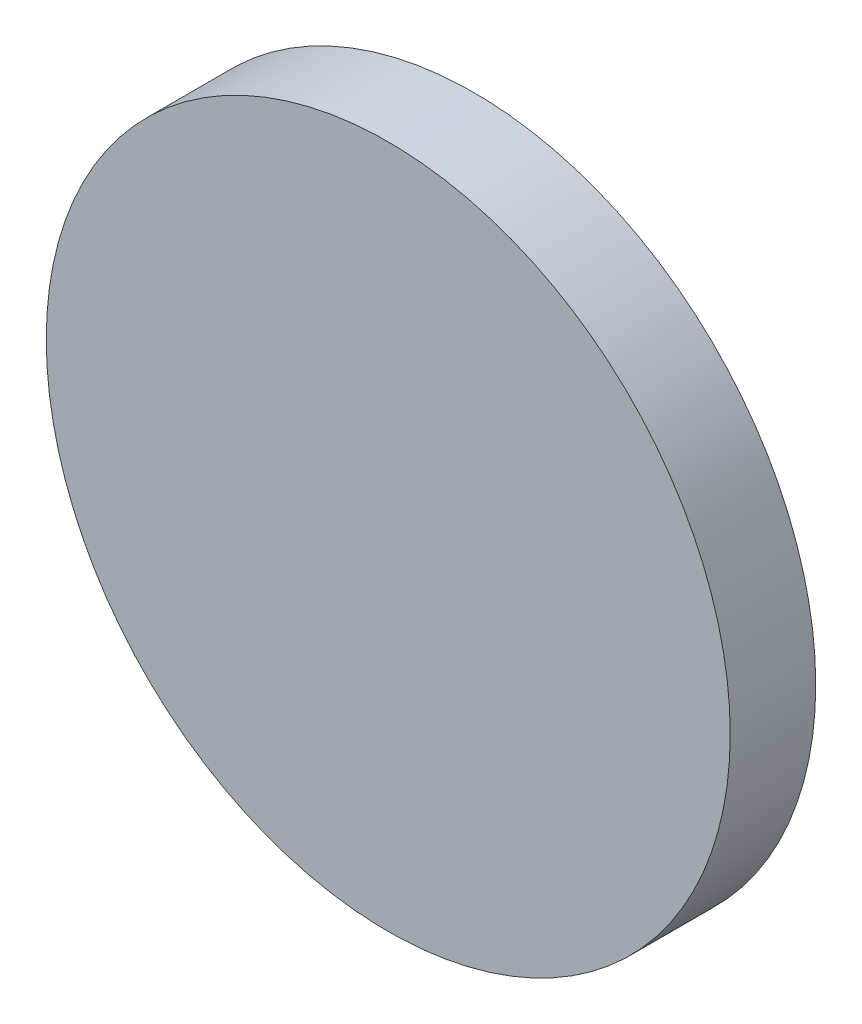
SolidWorks part; units mm, degrees
ref_plane "Plano frontal" through (0, 0, 0) normal (0, 0, 1) x (1, 0, 0)
ref_plane "Plano superior" through (0, 0, 0) normal (0, 1, 0) x (1, 0, 0)
ref_plane "Plano direito" through (0, 0, 0) normal (1, 0, 0) x (0, 0, -1)
sketch "Esboço1" plane through (0, 0, 0) normal (0, 0, 1) x (1, 0, 0)
  circle A0 centre (0, 0) radius 8
  dimension "D1" = 16
extrude "Ressalto-extrusão1" add sketch "Esboço1" along normal blind 2
